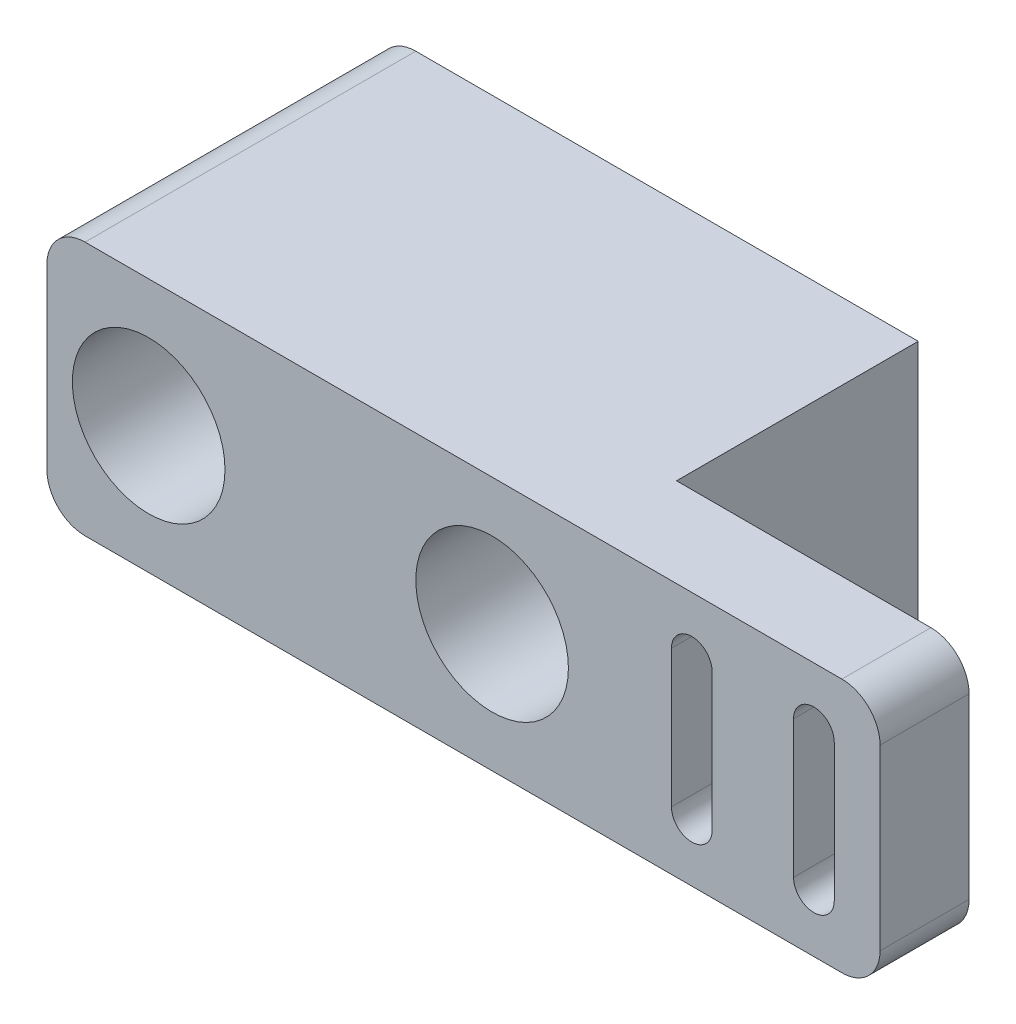
SolidWorks part; units mm, degrees
material "ABS"
ref_plane "Front Plane" through (0, 0, 0) normal (0, 0, 1) x (1, 0, 0)
ref_plane "Top Plane" through (0, 0, 0) normal (0, 1, 0) x (1, 0, 0)
ref_plane "Right Plane" through (0, 0, 0) normal (1, 0, 0) x (0, 0, -1)
sketch "Sketch1" plane through (0, 0, 0) normal (0, 0, 1) x (1, 0, 0)
  line L0 (49.1, 15.4) -> (49.1, 4.6)
  line L1 (3, 0) -> (62.5, 0)
  line L2 (0, 3) -> (0, 17)
  line L3 (3, 20) -> (62.5, 20)
  line L4 (65.5, 3) -> (65.5, 17)
  line L5 (52.3, 15.4) -> (52.3, 4.6)
  line L6 (0, 10) -> (65.5, 10) construction
  line L7 (58.7, 15.4) -> (58.7, 4.6)
  line L8 (61.9, 15.4) -> (61.9, 4.6)
  circle A0 centre (8, 10) radius 5 construction
  circle A1 centre (35, 10) radius 5 construction
  arc A2 (52.3, 15.4) -> (49.1, 15.4) centre (50.7, 15.4) ccw
  arc A3 (49.1, 4.6) -> (52.3, 4.6) centre (50.7, 4.6) ccw
  arc A4 (61.9, 15.4) -> (58.7, 15.4) centre (60.3, 15.4) ccw
  arc A5 (58.7, 4.6) -> (61.9, 4.6) centre (60.3, 4.6) ccw
  arc A6 (62.5, 20) -> (65.5, 17) centre (62.5, 17) cw
  arc A7 (65.5, 3) -> (62.5, 0) centre (62.5, 3) cw
  arc A8 (3, 0) -> (0, 3) centre (3, 3) cw
  arc A9 (0, 17) -> (3, 20) centre (3, 17) cw
  circle A10 centre (8, 10) radius 2.6
  circle A11 centre (35, 10) radius 2.6
  point P19 (52.3, 10)
  point P26 (65.5, 20)
  point P31 (0, 0)
  point P34 (0, 20)
  dimension "D3" = 3.2
  dimension "D7" = 10
  dimension "D8" = 8
  dimension "D9" = 27
  dimension "D10" = 3
  dimension "D11" = 5.2
  dimension "D1" = 65.5
  dimension "D2" = 20
  dimension "D4" = 10.8
  dimension "D5" = 5.2
  dimension "D6" = 2
extrude "Boss-Extrude1" add sketch "Sketch1" against normal blind 7
sketch "Sketch2" plane through (0, 0, -7) normal (0, 0, -1) x (-1, 0, 0)
  line L0 (-42.5, 20) -> (-42.5, 0)
  line L1 (-62.5, 20) -> (-3, 20) construction
  line L2 (-3, 0) -> (-62.5, 0) construction
  line L3 (0, 17) -> (0, 3) construction
  line L4 (-42.5, 20) -> (-3, 20)
  line L5 (0, 17) -> (0, 3)
  line L6 (-3, 0) -> (-42.5, 0)
  line L7 (-65.5, 3) -> (-65.5, 17) construction
  arc A0 (0, 17) -> (-3, 20) centre (-3, 17) ccw construction
  arc A1 (-3, 0) -> (0, 3) centre (-3, 3) ccw construction
  arc A2 (0, 17) -> (-3, 20) centre (-3, 17) ccw
  arc A3 (-3, 0) -> (0, 3) centre (-3, 3) ccw
  dimension "D1" = 23
extrude "Boss-Extrude2" add sketch "Sketch2" along normal blind 19
sketch "Sketch3" plane through (0, 0, -7) normal (0, 0, 1) x (1, 0, 0)
  circle A0 centre (8, 10) radius 2.6 construction
  circle A1 centre (35, 10) radius 2.6 construction
  circle A2 centre (8, 10) radius 2.6
  circle A3 centre (35, 10) radius 2.6
extrude "Cut-Extrude1" cut sketch "Sketch3" against normal up to surface (19 mm away) up to face at (14.9596, 10, -26)
sketch "Sketch4" plane through (0, 0, 0) normal (0, 0, 1) x (1, 0, 0)
  circle A0 centre (8, 10) radius 6
  circle A1 centre (35, 10) radius 6
  dimension "D1" = 12
extrude "Cut-Extrude2" cut sketch "Sketch4" against normal blind 14
